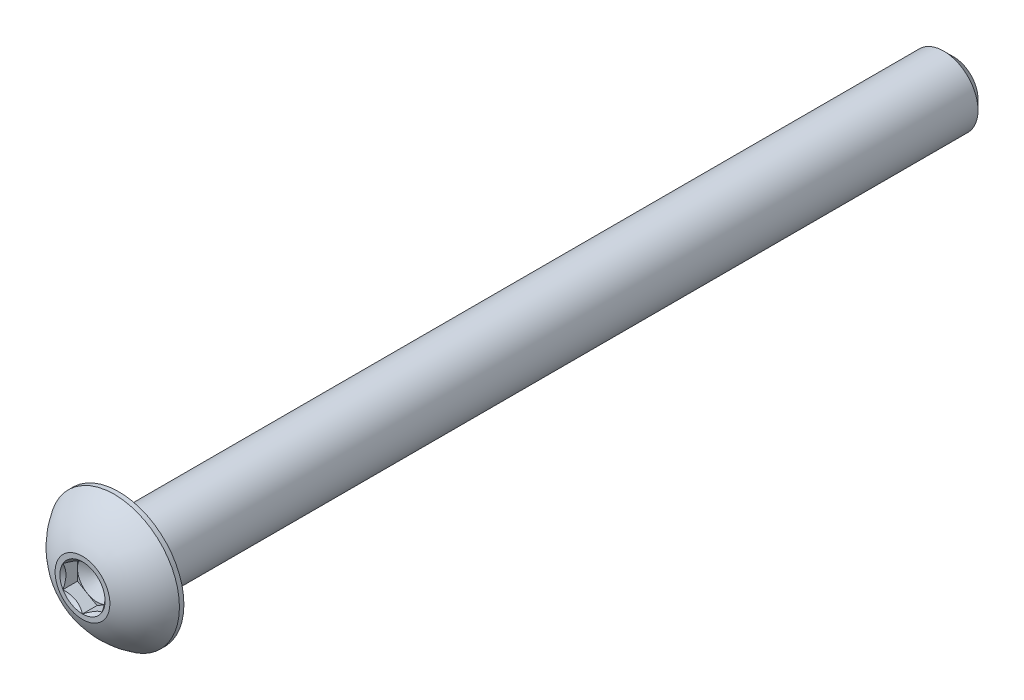
SolidWorks part; units mm, degrees
ref_plane "Front Plane" through (0, 0, 0) normal (0, 0, 1) x (1, 0, 0)
ref_plane "Top Plane" through (0, 0, 0) normal (0, 1, 0) x (1, 0, 0)
ref_plane "Right Plane" through (0, 0, 0) normal (1, 0, 0) x (0, 0, -1)
sketch "Sketch1" plane through (0, 0, 0) normal (1, 0, 0) x (0, 0, -1)
  line L0 (-26.5049, 0) -> (26.5049, 0) construction
  line L1 (-24.2951, 3.9624) -> (-24.2951, -3.9624) construction
  line L2 (-26.5049, 1.1906) -> (-26.5049, -1.1906) construction
  line L3 (26.5049, 2.0828) -> (26.5049, -2.0828) construction
  line L4 (26.4553, 2.1687) -> (26.8522, 1.4813) construction
  line L5 (26.8522, 1.4813) -> (27.249, 2.1687) construction
  line L6 (27.249, 2.1687) -> (26.4553, 2.1687) construction
  line L7 (26.8522, 2.1687) -> (26.8522, 2.0828) construction
  line L8 (26.8522, 1.4813) -> (26.8522, 1.5672) construction
  line L9 (26.8026, 1.5672) -> (26.9018, 1.5672)
  line L10 (-26.5049, 1.6669) -> (-26.5049, -1.6669) construction
  line L11 (-24.2951, 3.9624) -> (-24.5672, 3.9624) construction
  line L12 (-26.5049, 1.1906) -> (-25.621, 1.1906) construction
  line L13 (-25.621, 1.1906) -> (-24.9336, 0) construction
  point P5 (-24.2951, 0)
  point P10 (23.7268, -2.0828)
  dimension "Drive Size" = 2.3813
  dimension "Head Diameter" = 7.9248
  dimension "Head Height" = 2.2098
  dimension "Diameter" = 4.1656
  dimension "Thread Length" = 50.8
  dimension "D1" = 2.7781
  dimension "Pitch" = 0.7937
  dimension "D2" = 0.0992
  dimension "D3" = 3.3337
  dimension "D4" = 0.2721
  dimension "D5" = 60
  dimension "D6" = 0.8839
sketch "Sketch2" plane through (0, 0, 0) normal (1, 0, 0) x (0, 0, -1)
  line L0 (-26.5049, 1.1906) -> (-26.5049, 1.6669)
  line L1 (-24.5672, 3.9624) -> (-24.2951, 3.9624)
  line L2 (-24.2951, 3.9624) -> (-24.2951, 2.0828)
  line L3 (-24.2951, 3.9624) -> (-24.2951, -3.9624) construction
  line L4 (-24.2951, 2.0828) -> (25.9096, 2.0828)
  line L5 (26.5049, 1.4875) -> (26.5049, 0)
  line L6 (-26.5049, 1.1906) -> (-25.621, 1.1906)
  line L7 (-25.621, 1.1906) -> (-24.9336, 0)
  line L8 (26.5049, 0) -> (-24.9336, 0)
  line L9 (25.9096, 2.0828) -> (26.5049, 1.4875)
  line L10 (25.9096, -2.0828) -> (25.9096, 2.0828) construction
  arc A0 (-24.5672, 3.9624) -> (-26.5049, 1.6669) centre (-22.2016, 0) ccw
  point P13 (26.5049, 2.0828)
  point P25 (25.9096, 0)
  dimension "D1" = 0.5953
  dimension "D2" = 45
revolve "Revolve1" add sketch "Sketch2" angle 360 about L0
sketch "Sketch3" plane through (0, 0, 0) normal (0, 0, 1) x (1, 0, 0)
  line L1 (0, 1.3748) -> (-1.1906, 0.6874)
  line L2 (-1.1906, 0.6874) -> (-1.1906, -0.6874)
  line L3 (-1.1906, -0.6874) -> (0, -1.3748)
  line L4 (0, -1.3748) -> (1.1906, -0.6874)
  line L5 (1.1906, -0.6874) -> (1.1906, 0.6874)
  line L6 (1.1906, 0.6874) -> (0, 1.3748)
  circle A0 centre (0, 0) radius 1.1906 construction
extrude "Cut-Extrude1" cut sketch "Sketch3" along normal through all from vertex at 25.621 starting at point (0, 1.1906, 25.621)
sketch "Sketch4" plane through (0, 0, 26.5049) normal (0, 0, 1) x (1, 0, 0)
  circle A0 centre (0, 0) radius 1.3748
extrude "Cut-Extrude2" cut sketch "Sketch4" against normal up to next (53.0098 mm away) draft 45
sketch "Sketch9" plane through (0, 0, 0) normal (1, 0, 0) x (0, 0, -1)
  line L0 (26.5049, -2.0828) -> (-24.2951, -2.0828) construction
  line L1 (-24.2951, -2.0828) -> (25.9096, -2.0828) construction
  line L2 (26.5049, -1.4875) -> (26.5049, 1.4875) construction
  line L3 (-24.2951, -2.0828) -> (-24.2951, 2.0828) construction
  point P9 (25.3143, -2.0828)
  dimension "D1" = 1.1906
sketch "Sketch5" plane through (0, 0, -26.5049) normal (0, 0, -1) x (-1, 0, 0)
  circle A0 centre (0, 0) radius 2.0828
curve "Helix/Spiral1" pitch 0.7937 height 51.5938 turns 65
equation "\"D2@Sketch1\"=\"Pitch@Sketch1\"*.125"
equation "\"D1@Sketch1\"=\"Pitch@Sketch1\"*3.5"
equation "\"D3@Sketch1\"=\"Drive Size@Sketch1\"*1.4"
equation "\"D4@Sketch1\"=(\"D3@Sketch1\"-\"Drive Size@Sketch1\")/3.5"
equation "\"D6@Sketch1\"=\"Head Height@Sketch1\"*.40"
equation "\"D1@Sketch2\"=\"Pitch@Sketch1\"*.750"
equation "\"D4@Helix/Spiral1\"=\"Pitch@Sketch1\""
equation "\"D3@Helix/Spiral1\"=\"D4@Helix/Spiral1\"+\"Thread Length@Sketch1\""
equation "\"D1@Sketch9\"=\"Pitch@Sketch1\"*1.5"
